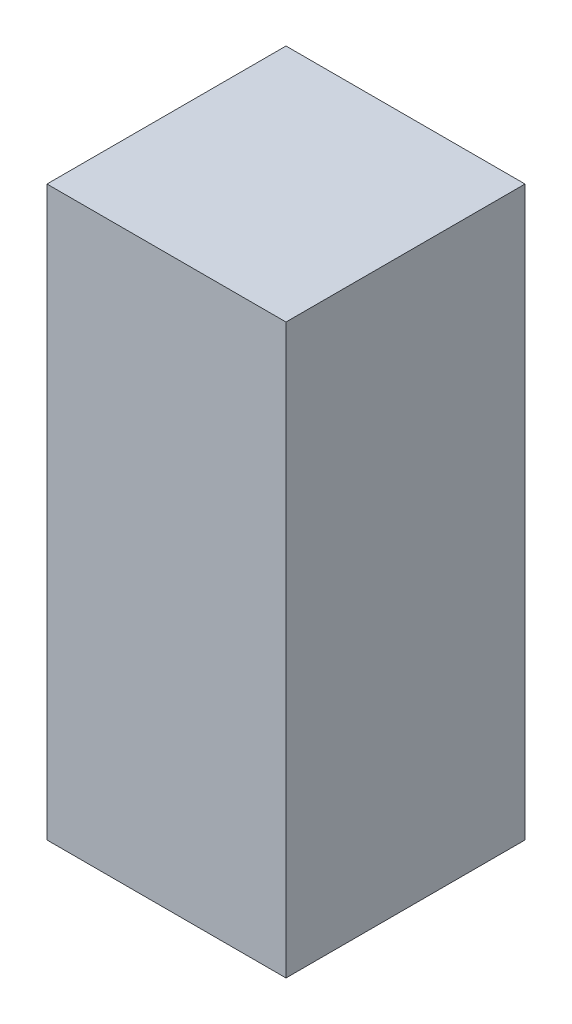
SolidWorks part; units mm, degrees
material "7075-T6 (SN)"
ref_plane "Front Plane" through (0, 0, 0) normal (0, 0, 1) x (1, 0, 0)
ref_plane "Top Plane" through (0, 0, 0) normal (0, 1, 0) x (1, 0, 0)
ref_plane "Right Plane" through (0, 0, 0) normal (1, 0, 0) x (0, 0, -1)
sketch "Sketch1" plane through (0, 0, 0) normal (0, 1, 0) x (1, 0, 0)
  line L1 (-3, -3) -> (3, -3)
  line L2 (-3, -3) -> (-3, 3)
  line L3 (-3, 3) -> (3, 3)
  line L4 (3, -3) -> (3, 3)
  line L5 (-3, -3) -> (3, 3) construction
  line L6 (-3, 3) -> (3, -3) construction
  point P0 (0, 0)
  dimension "D1" = 6
extrude "Boss-Extrude1" add sketch "Sketch1" along normal blind 14.26
sketch "Sketch3" plane through (-3, 0, 0) normal (-1, 0, 0) x (0, 0, 1)
  line L0 (-3, 14.26) -> (-3, 0) construction
  line L2 (-3, 0) -> (3, 0) construction
  circle A0 centre (0, 3) radius 1.25
  dimension "D3" = 2.5
  dimension "D1" = 3
  dimension "D2" = 3
